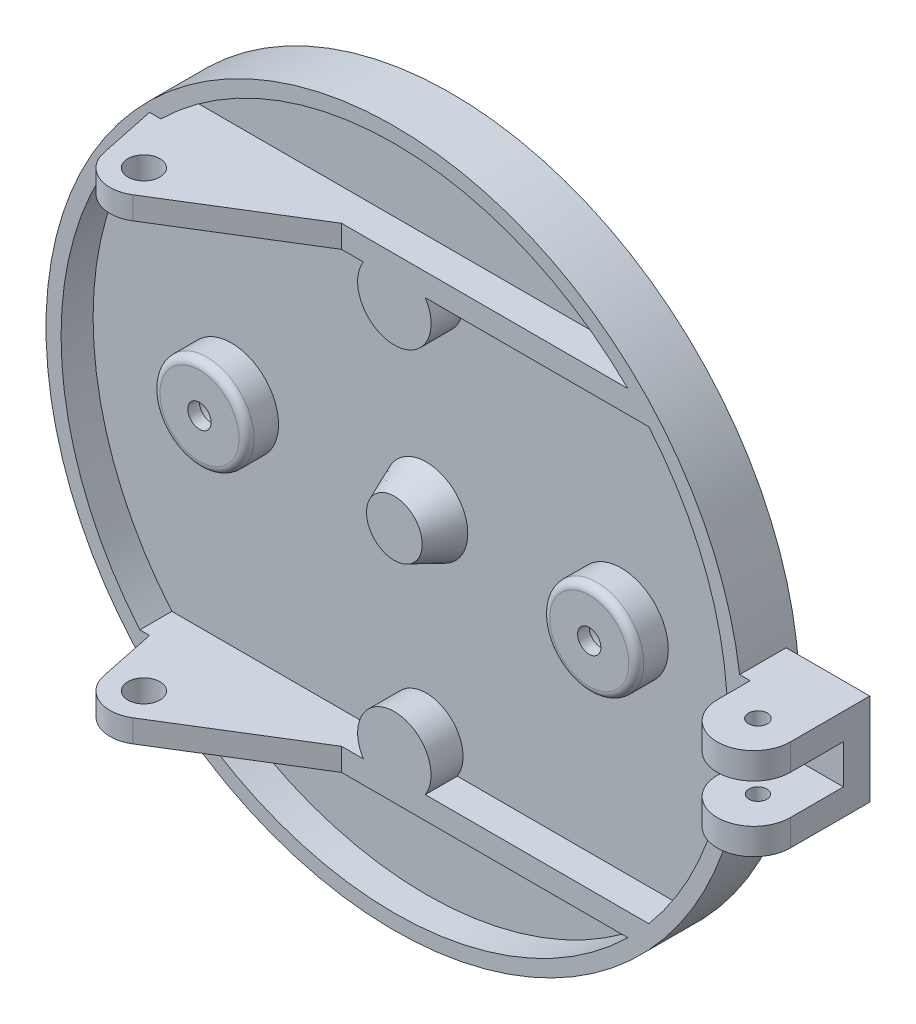
SolidWorks part; units mm, degrees
ref_plane "Plan de face" through (0, 0, 0) normal (0, 0, 1) x (1, 0, 0)
ref_plane "Plan de dessus" through (0, 0, 0) normal (0, 1, 0) x (1, 0, 0)
ref_plane "Plan de droite" through (0, 0, 0) normal (1, 0, 0) x (0, 0, -1)
sketch "Esquisse1" plane through (0, 0, 0) normal (0, 0, 1) x (1, 0, 0)
  circle A0 centre (0, 0) radius 92.5
  dimension "D1" = 185
extrude "Boss.-Extru.1" add sketch "Esquisse1" along normal blind 15.1
sketch "Esquisse2" plane through (0, 0, 15.1) normal (0, 0, 1) x (1, 0, 0)
  circle A2 centre (0, 0) radius 88.5
  circle A3 centre (0, 0) radius 88.5
  dimension "D1" = 4
extrude "Enlèv. mat.-Extru.1" cut sketch "Esquisse2" against normal blind 8.5
sketch "Esquisse3" plane through (0, 0, 15.1) normal (0, 0, 1) x (1, 0, 0)
  line L0 (0, 0) -> (113.6187, 0) construction
  line L1 (-62.0128, 63.14) -> (62.0128, 63.14)
  line L2 (-67.5816, -57.14) -> (-8.2158, -57.14)
  line L3 (-67.5816, 57.14) -> (-8.2158, 57.14)
  line L4 (-62.0128, -63.14) -> (62.0128, -63.14)
  line L5 (8.2158, 57.14) -> (67.5816, 57.14)
  line L6 (8.2158, -57.14) -> (67.5816, -57.14)
  circle A0 centre (0, 0) radius 88.5 construction
  arc A1 (67.5816, 57.14) -> (62.0128, 63.14) centre (0, 0) ccw
  arc A2 (-62.0128, 63.14) -> (-67.5816, 57.14) centre (0, 0) ccw
  arc A3 (-62.0128, -63.14) -> (-67.5816, -57.14) centre (0, 0) cw
  arc A4 (67.5816, -57.14) -> (62.0128, -63.14) centre (0, 0) cw
  arc A5 (-8.2158, 57.14) -> (8.2158, 57.14) centre (0, 51.89) ccw
  arc A6 (-8.2158, -57.14) -> (8.2158, -57.14) centre (0, -51.89) cw
  dimension "D3" = 19.5
  dimension "D1" = 6
  dimension "D2" = 63.14
  dimension "D4" = 5.25
extrude "Boss.-Extru.2" add sketch "Esquisse3" against normal up to surface (8.5 mm away) up to face at (88.5, 0, 6.6)
sketch "Esquisse4" plane through (0, 0, 6.6) normal (0, 0, 1) x (1, 0, 0)
  circle A0 centre (0, 0) radius 11
  dimension "D1" = 22
extrude "Boss.-Extru.3" add sketch "Esquisse4" along normal up to surface (8.5 mm away) draft 23
sketch "Esquisse5" plane through (0, 0, 0) normal (0, 1, 0) x (1, 0, 0)
  line L0 (90.5, -2.75) -> (113.9, -2.75)
  line L1 (113.9, -2.75) -> (113.9, -23.85)
  line L2 (90.5, -15.1) -> (94.5, -15.1)
  line L3 (-92.5, -15.1) -> (92.5, -15.1) construction
  line L4 (94.5, -15.1) -> (94.5, -23.85)
  line L5 (90.5, -15.1) -> (90.5, -2.75)
  line L6 (92.5, 0) -> (-92.5, 0) construction
  line L7 (92.5, -15.1) -> (92.5, 0) construction
  arc A0 (94.5, -23.85) -> (113.9, -23.85) centre (104.2, -23.85) ccw
  dimension "D1" = 2.75
  dimension "D2" = 2
  dimension "D3" = 19.4
  dimension "D4" = 23.4
  dimension "D5" = 21.1
extrude "Boss.-Extru.4" add sketch "Esquisse5" along normal mid plane 24.4
sketch "Esquisse6" plane through (113.9, 0, 0) normal (1, 0, 0) x (0, 0, -1)
  line L0 (-23.85, 12.2) -> (-2.75, 12.2) construction
  line L1 (-9.75, 5.2) -> (-33.55, 5.2)
  line L2 (-9.75, 5.2) -> (-9.75, -5.2)
  line L3 (-9.75, -5.2) -> (-33.55, -5.2)
  line L4 (-33.55, 5.2) -> (-33.55, -5.2)
  line L5 (-23.85, -12.2) -> (-2.75, -12.2) construction
  line L6 (-2.75, 12.2) -> (-2.75, -12.2) construction
  line L7 (-33.55, 12.2) -> (-33.55, -12.2) construction
  point P8 (-2.75, 0)
  dimension "D1" = 7
  dimension "D2" = 7
  dimension "D3" = 7
extrude "Enlèv. mat.-Extru.2" cut sketch "Esquisse6" against normal up to surface (21.5463 mm away)
hole_wizard "Trou taraudé M61" positions "Esquisse8" profile "Esquisse7" tap size "M6" standard "ISO"
sketch "Esquisse8" plane through (0, 12.2, 0) normal (0, 1, 0) x (-1, 0, 0)
  line L0 (-113.9, 23.85) -> (-113.9, 2.75) construction
  line L1 (-90.5, 2.75) -> (-113.9, 2.75) construction
  point P0 (-104.2, 22.75)
  dimension "D1" = 9.7
  dimension "D2" = 20
sketch "Esquisse7" plane through (104.2, 12.2, 22.75) normal (1, 0, 0) x (0, 0, 1)
  line L0 (0, 0) -> (0, 14.5022)
  line L1 (0, 14.5022) -> (2.5, 13)
  line L2 (2.5, 13) -> (2.5, 0)
  line L5 (2.5, 0) -> (0, 0)
  line L10 (0, 14.5022) -> (-2.5, 13) construction
  line L11 (0, -6.35) -> (0, 107.95) construction
  dimension "Diamètre du trou pour taraudage" = 5
  dimension "Profondeur du trou pour taraudage" = 13
  dimension "Angle de pointe" = 118
cosmetic thread "Filetage de perçage1" parameters "D1"=7, "D2"=6
sketch "Esquisse9" plane through (0, -5.2, 0) normal (0, 1, 0) x (1, 0, 0)
  circle A0 centre (104.2, -22.75) radius 2.375
  dimension "D1" = 4.75
extrude "Enlèv. mat.-Extru.3" cut sketch "Esquisse9" against normal through all
sketch "Esquisse10" plane through (0, 63.14, 0) normal (0, 1, 0) x (1, 0, 0)
  line L0 (-14, -15.1) -> (-48.2722, -36.2582)
  line L1 (62.0128, -15.1) -> (-62.0128, -15.1) construction
  line L2 (-61.8115, -30.4324) -> (-65, -15.1)
  line L3 (-92.5, -15.1) -> (91.6919, -15.1) construction
  line L4 (0, -6.6) -> (0, -15.1) construction
  line L5 (-14, -15.1) -> (-65, -15.1)
  arc A0 (-61.8115, -30.4324) -> (-48.2722, -36.2582) centre (-53, -28.6) ccw
  circle A1 centre (-53, -28.6) radius 4.25
  dimension "D4" = 18
  dimension "D6" = 8.5
  dimension "D1" = 51
  dimension "D2" = 12
  dimension "D3" = 14
  dimension "D5" = 13.5
extrude "Boss.-Extru.5" add sketch "Esquisse10" against normal blind 6
mirror "Symétrie1" about plane through (0, 0, 0) normal (0, 1, 0) of "Boss.-Extru.5"
sketch "Esquisse11" plane through (0, 0, 6.6) normal (0, 0, 1) x (1, 0, 0)
  circle A0 centre (-51.75, 0) radius 12.5
  circle A1 centre (51.75, 0) radius 12.5
  circle A2 centre (-51.75, 0) radius 3.65 construction
  circle A3 centre (51.75, 0) radius 3.65 construction
  dimension "D1" = 25
  dimension "D2" = 25
extrude "Boss.-Extru.6" add sketch "Esquisse11" along normal up to surface (8.5 mm away) up to face at (-15.8, 0, 15.1)
fillet "Congé1" radius 2 2 edges at (-39.25, 0, 15.1) (64.25, 0, 15.1)
sketch "Esquisse12" plane through (0, 0, 0) normal (0, 1, 0) x (1, 0, 0)
  line L0 (57.9, 0) -> (57.9, -12)
  line L1 (92.5, 0) -> (-92.5, 0) construction
  line L2 (57.9, -12) -> (54.85, -12)
  line L3 (54.85, -12) -> (54.85, -15.1)
  line L4 (-92.5, -15.1) -> (91.6919, -15.1) construction
  line L5 (57.9, 0) -> (51.75, 0)
  line L6 (51.75, -15.1) -> (54.85, -15.1)
  line L7 (51.75, 5.6117) -> (51.75, -25.3425) construction
  line L8 (51.75, -13.1) -> (51.75, -6.6) construction
  line L9 (51.75, 0) -> (51.75, -15.1)
  dimension "D1" = 12.3
  dimension "D2" = 6.2
  dimension "D3" = 12
revolve "Enlèvement de matière-Révolution1" cut sketch "Esquisse12" angle 360 about L7
pattern_circular "Répétition circulaire1" count 2 over 360 about axis through (0, 0, 0) along (0, 0, 1) of "Enlèvement de matière-Révolution1"
